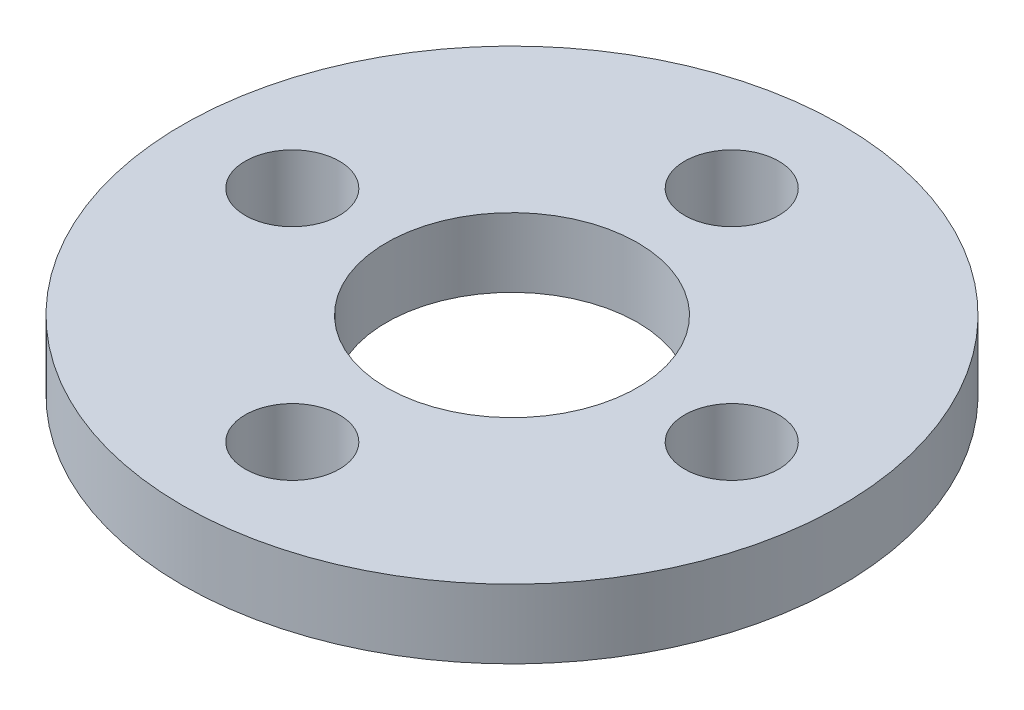
SolidWorks part; units mm, degrees
ref_plane "Front Plane" through (0, 0, 0) normal (0, 0, 1) x (1, 0, 0)
ref_plane "Top Plane" through (0, 0, 0) normal (0, 1, 0) x (1, 0, 0)
ref_plane "Right Plane" through (0, 0, 0) normal (1, 0, 0) x (0, 0, -1)
sketch "Sketch1" plane through (0, 0, 0) normal (0, 1, 0) x (1, 0, 0)
  circle A0 centre (0, 0) radius 10.5
  dimension "D1" = 21
extrude "Boss-Extrude1" add sketch "Sketch1" along normal blind 2.2
sketch "Sketch2" plane through (0, 2.2, 0) normal (0, 1, 0) x (1, 0, 0)
  line L0 (0, 0) -> (0, 7) construction
  circle A0 centre (0, 0) radius 4
  circle A1 centre (0, 7) radius 1.5
  circle A2 centre (7, 0) radius 1.5
  circle A3 centre (0, -7) radius 1.5
  circle A4 centre (-7, 0) radius 1.5
  point P14 (0, 0)
  dimension "D1" = 4
extrude "Cut-Extrude1" cut sketch "Sketch2" against normal blind 2.2
